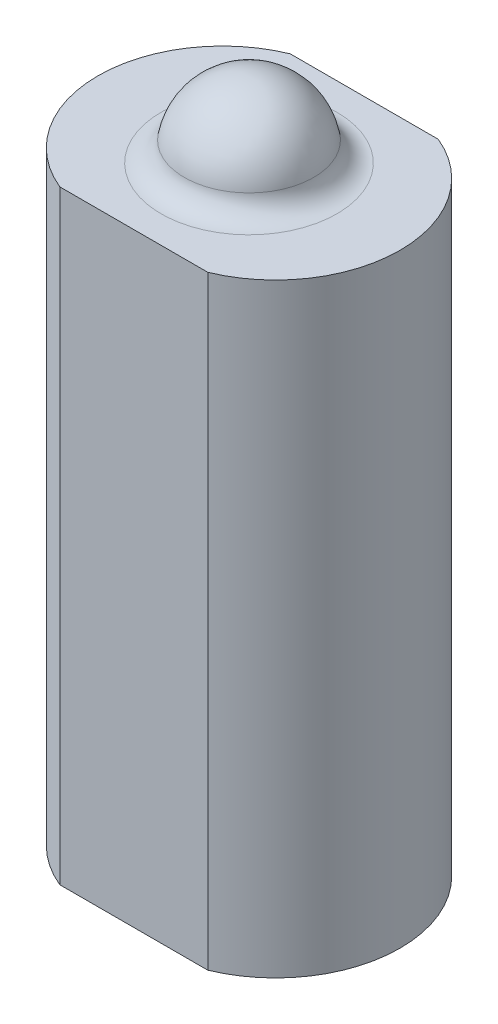
SolidWorks part; units mm, degrees
ref_plane "Front Plane" through (0, 0, 0) normal (0, 0, 1) x (1, 0, 0)
ref_plane "Top Plane" through (0, 0, 0) normal (0, 1, 0) x (1, 0, 0)
ref_plane "Right Plane" through (0, 0, 0) normal (1, 0, 0) x (0, 0, -1)
sketch "Sketch1" plane through (0, 0, 0) normal (0, 1, 0) x (1, 0, 0)
  line L0 (-9.7912, 15.25) -> (9.7912, 15.25)
  line L1 (9.7912, 15.25) -> (9.7912, -15.25) construction
  line L2 (9.7912, -15.25) -> (-9.7912, -15.25)
  line L3 (-9.7912, -15.25) -> (-9.7912, 15.25) construction
  line L4 (-3.5053, 0) -> (3.5053, 0) construction
  arc A0 (-9.7912, 15.25) -> (-9.7912, -15.25) centre (-3.5053, 0) ccw
  arc A1 (9.7912, 15.25) -> (9.7912, -15.25) centre (3.5053, 0) cw
  point P2 (0, 15.25)
  point P5 (9.7912, 0)
  point P8 (-20, 0)
  point P10 (20, 0)
  point P11 (0, 0)
  dimension "D1" = 40
  dimension "D2" = 30.5
extrude "Boss-Extrude1" add sketch "Sketch1" along normal blind 80
sketch "Sketch2" plane through (0, 80, 0) normal (0, 1, 0) x (1, 0, 0)
  line L0 (0, 0) -> (0, 10)
  circle A0 centre (0, 0) radius 10 construction
  dimension "D1" = 20
sketch "Sketch4" plane through (0, 0, 0) normal (1, 0, 0) x (0, 0, -1)
  line L0 (0, 80) -> (10, 80) construction
  line L1 (0, 80) -> (11.6419, 80)
  line L2 (0, 80) -> (0, 89.9191)
  arc A0 (0, 89.9191) -> (8.5603, 82.6255) centre (0, 81.2487) cw
  arc A1 (8.5603, 82.6255) -> (11.6419, 80) centre (11.6419, 83.1212) ccw
  point P7 (0, 87.8849)
  point P8 (0, 90.9185)
  point P9 (11.6419, 80)
  point P11 (0, 89.9191)
revolve "Revolve1" add sketch "Sketch4" angle 360 about L2
sketch "Sketch5" plane through (0, 0, 0) normal (0, -1, 0) x (1, 0, 0)
  circle A0 centre (0, 0) radius 10.2
  dimension "D1" = 20.4
